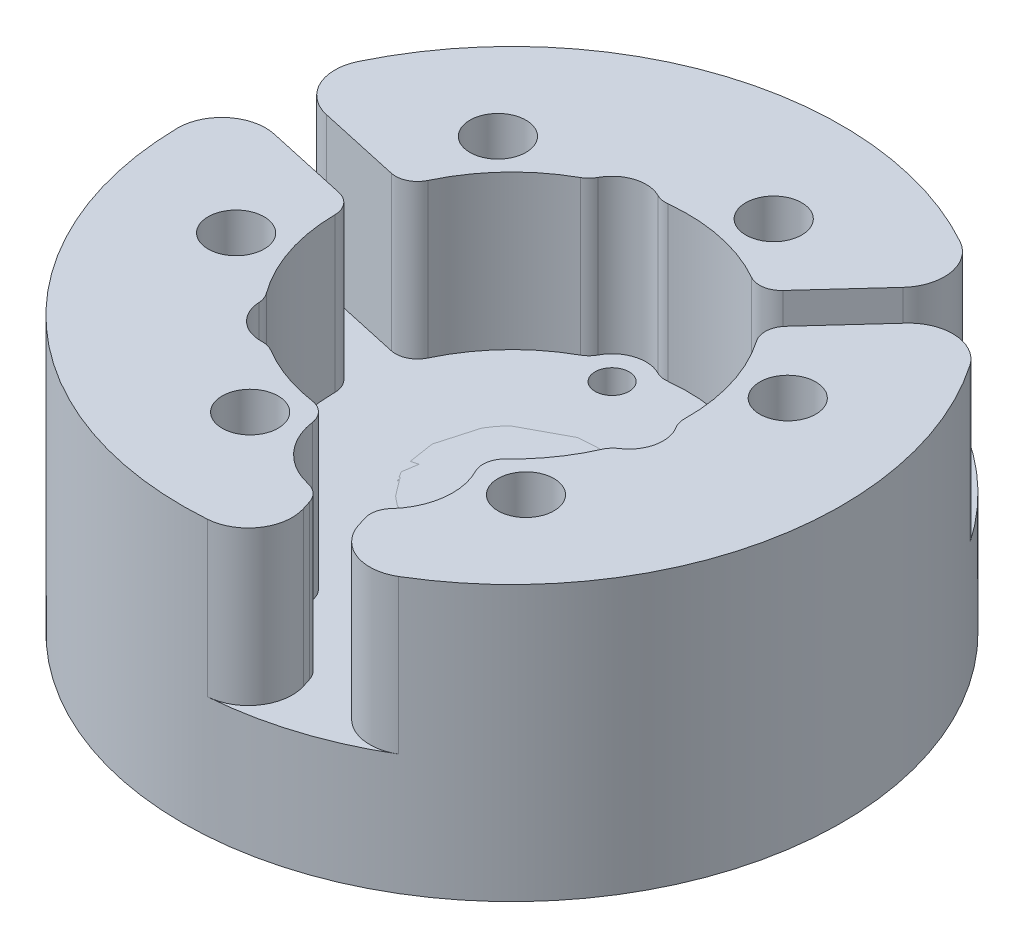
SolidWorks part; units mm, degrees
ref_plane "前视基准面" through (0, 0, 0) normal (0, 0, 1) x (1, 0, 0)
ref_plane "上视基准面" through (0, 0, 0) normal (0, 1, 0) x (1, 0, 0)
ref_plane "右视基准面" through (0, 0, 0) normal (1, 0, 0) x (0, 0, -1)
other "Configuration Table"
sketch "草图1" plane through (0, 0, 0) normal (0, 1, 0) x (1, 0, 0)
  circle A0 centre (0, 0) radius 30
  dimension "D1" = 60
extrude "凸台-拉伸1" add sketch "草图1" along normal blind 25
sketch "草图3" plane through (0, 25, 0) normal (0, 1, 0) x (1, 0, 0)
  circle A12 centre (-14.7658, 13.4896) radius 2.55
  circle A13 centre (4.2994, 19.5324) radius 2.55
  circle A14 centre (19.0653, 6.0428) radius 2.55
  circle A15 centre (14.7658, -13.4896) radius 2.55
  circle A16 centre (-4.2994, -19.5324) radius 2.55
  circle A17 centre (-19.0653, -6.0428) radius 2.55
  point P15 (0, 0)
  dimension "D1" = 6
extrude "切除-拉伸2" cut sketch "草图3" against normal through all
sketch "草图2" plane through (0, 25, 0) normal (0, 1, 0) x (1, 0, 0)
  line L0 (-19.0653, -6.0428) -> (-4.2994, -19.5324) construction
  line L1 (-11.6824, -12.7876) -> (0, 0) construction
  line L2 (-4.2994, -19.5324) -> (14.7658, -13.4896) construction
  line L3 (-1.2898, -5.8597) -> (4.4298, -4.0469)
  line L4 (4.4298, -4.0469) -> (5.7196, 1.8128)
  line L5 (5.7196, 1.8128) -> (1.2898, 5.8597)
  line L14 (5.2332, -16.511) -> (-5.2019, 16.4123) construction
  line L15 (1.2898, 5.8597) -> (-4.4298, 4.0469)
  line L16 (-4.4298, 4.0469) -> (-5.7196, -1.8128)
  line L17 (-5.7196, -1.8128) -> (-1.2898, -5.8597)
  circle A0 centre (0, 0) radius 5.1962 construction
  circle A1 centre (-4.23, 13.3457) radius 1.55
  circle A2 centre (13.6727, -3.0096) radius 1.55
  circle A3 centre (-9.4427, -10.3361) radius 1.55
  point P28 (0, 0)
  dimension "D1" = 3.1
  dimension "D2" = 14
  dimension "D3" = 6
  dimension "D4" = 3
extrude "切除-拉伸1" cut sketch "草图2" against normal through all
sketch "草图5" plane through (0, 25, 0) normal (0, 1, 0) x (1, 0, 0)
  line L3 (-1.0891, -13.94) -> (0.2828, -18.2683)
  line L4 (5.278, -21.4057) -> (8.0161, -20.5379)
  line L5 (10.2921, -15.0959) -> (8.9202, -10.7675)
  line L6 (-1.0891, -13.94) -> (0.2828, -18.2683)
  line L7 (5.278, -21.4057) -> (8.0161, -20.5379)
  line L8 (10.2921, -15.0959) -> (8.9202, -10.7675)
  arc A7 (0.2828, -18.2683) -> (2.0868, -20.8437) centre (5.2874, -16.6821) ccw
  arc A8 (2.0868, -20.8437) -> (5.278, -21.4057) centre (4.2206, -18.0693) ccw
  arc A9 (8.0161, -20.5379) -> (10.3009, -18.2402) centre (6.9586, -17.2015) ccw
  arc A10 (10.3009, -18.2402) -> (10.2921, -15.0959) centre (5.2874, -16.6821) ccw
  arc A11 (9.4319, -8.3546) -> (8.9202, -10.7675) centre (11.3034, -10.0122) ccw
  arc A12 (9.4319, -8.3546) -> (-2.8974, -12.2624) centre (0, 0) ccw
  arc A13 (-1.0891, -13.94) -> (-2.8974, -12.2624) centre (-3.4722, -14.6954) ccw
  arc A14 (0.2828, -18.2683) -> (2.0868, -20.8437) centre (5.2874, -16.6821) ccw
  arc A15 (2.0868, -20.8437) -> (5.278, -21.4057) centre (4.2206, -18.0693) ccw
  arc A16 (8.0161, -20.5379) -> (10.3009, -18.2402) centre (6.9586, -17.2015) ccw
  arc A17 (10.3009, -18.2402) -> (10.2921, -15.0959) centre (5.2874, -16.6821) ccw
  arc A18 (9.4319, -8.3546) -> (8.9202, -10.7675) centre (11.3034, -10.0122) ccw
  arc A19 (9.4319, -8.3546) -> (-2.8974, -12.2624) centre (0, 0) ccw
  arc A20 (-1.0891, -13.94) -> (-2.8974, -12.2624) centre (-3.4722, -14.6954) ccw
  dimension "D1" = 0
sketch "草图6" plane through (0, 25, 0) normal (0, 1, 0) x (1, 0, 0)
  circle A1 centre (0, 0) radius 16
  circle A2 centre (5.2874, -16.6821) radius 6
extrude "切除-拉伸4" cut sketch "草图6" against normal blind 14
sketch "草图8" plane through (0, 11, 0) normal (0, 1, 0) x (1, 0, 0)
  line L0 (0, 0) -> (-15106.966, 47663.1889) construction
  line L1 (-4.4298, 4.0469) -> (1.2898, 5.8597) construction
  line L2 (0, 0) -> (33724.0494, 36914.6108) construction
  line L3 (1.2898, 5.8597) -> (5.7196, 1.8128) construction
  line L4 (0, 0) -> (48831.0154, -10748.5781) construction
  line L5 (5.7196, 1.8128) -> (4.4298, -4.0469) construction
  line L6 (-35.3499, 7.7811) -> (-10.9344, 2.4069) construction
  line L7 (-34.92, 9.7344) -> (-10.5044, 4.3601)
  line L8 (-35.7798, 5.8279) -> (-11.3643, 0.4536)
  line L9 (-5.7196, -1.8128) -> (-4.4298, 4.0469) construction
  line L10 (24.4136, 26.7233) -> (7.5516, 8.266) construction
  line L11 (25.8902, 25.3744) -> (9.0282, 6.9171)
  line L12 (22.937, 28.0723) -> (6.075, 9.615)
  line L13 (10.9363, -34.5045) -> (3.3828, -10.6729) construction
  line L14 (9.0298, -35.1088) -> (1.4763, -11.2772)
  line L15 (12.8428, -33.9002) -> (5.2893, -10.0686)
  arc A0 (-34.92, 9.7344) -> (-35.7798, 5.8279) centre (-35.3499, 7.7811) ccw
  arc A1 (-11.3643, 0.4536) -> (-10.5044, 4.3601) centre (-10.9344, 2.4069) ccw
  arc A2 (25.8902, 25.3744) -> (22.937, 28.0723) centre (24.4136, 26.7233) ccw
  arc A3 (6.075, 9.615) -> (9.0282, 6.9171) centre (7.5516, 8.266) ccw
  arc A4 (9.0298, -35.1088) -> (12.8428, -33.9002) centre (10.9363, -34.5045) ccw
  arc A5 (5.2893, -10.0686) -> (1.4763, -11.2772) centre (3.3828, -10.6729) ccw
  point P5 (-1.57, 4.9533)
  point P10 (3.5047, 3.8363)
  point P15 (5.0747, -1.117)
  point P18 (-23.1421, 5.094)
  point P29 (15.9826, 17.4947)
  point P36 (7.1595, -22.5887)
  point P41 (0, 0)
  arc M2 (9.7578, -12.6801) -> (-0.672, -15.9859) centre (0, 0) ccw
  arc M3 (-0.672, -15.9859) -> (9.7578, -12.6801) centre (5.2874, -16.6821) ccw
  dimension "D3" = 2
  dimension "D1" = 25
  dimension "D2" = 6
  dimension "D4" = 3
extrude "切除-拉伸5" cut sketch "草图8" against normal up to surface (14 mm away) contours L7 A0 L8 M2 | L14 A4 L15 M3 | L11 A2 L12 M2
sketch "草图9" plane through (0, 0, 0) normal (0, -1, 0) x (1, 0, 0)
  circle A6 centre (-4.2994, 19.5324) radius 5.05
  circle A7 centre (14.7658, 13.4896) radius 5.05
  circle A8 centre (19.0653, -6.0428) radius 5.05
  circle A9 centre (4.2994, -19.5324) radius 5.05
  circle A10 centre (-14.7658, -13.4896) radius 5.05
  circle A11 centre (-19.0653, 6.0428) radius 5.05
  point P20 (0, 0)
  dimension "D1" = 6
extrude "切除-拉伸6" cut sketch "草图9" against normal blind 6
sketch "草图11" plane through (0, 25, 0) normal (0, 1, 0) x (1, 0, 0)
  circle A0 centre (-9.4427, -10.3361) radius 3.1
  circle A1 centre (13.6727, -3.0096) radius 3.1
  circle A2 centre (-4.23, 13.3457) radius 3.1
extrude "切除-拉伸7" cut sketch "草图11" against normal up to surface (14 mm away) up to face at (0.9454, 11, 2.9828)
fillet "圆角1" radius 4 6 edges at (-29.6634, 18, -4.4816) (10.9505, 18, 27.93) (21.666, 18, -20.7505) (18.7128, 18, -23.4485) (-28.8035, 18, -8.388) (7.1375, 18, 29.1386)
fillet "圆角2" radius 1 6 edges at (-4.4298, 5.5, -4.0469) (1.2898, 5.5, -5.8597) (5.7196, 5.5, -1.8128) (-1.2898, 5.5, 5.8597) (-5.7196, 5.5, 1.8128) (4.4298, 5.5, 4.0469)
fillet "圆角3" radius 2 14 edges at (-15.9333, 18, -1.4593) (-15.0734, 18, -5.3658) (-2.3675, 18, -15.8239) (-7.1799, 18, -14.2986) (9.2305, 18, -13.069) (14.8876, 18, 5.8616) (15.9729, 18, 0.9313) (9.7578, 18, 12.6801) (-0.672, 18, 15.9859) (8.9031, 18, 21.4703) (5.0901, 18, 22.6789) (-12.5201, 18, 9.9623) (-8.793, 18, 13.3672) (12.1836, 18, -10.3711)
sketch "草图12" plane through (0, 11, 0) normal (0, 1, 0) x (1, 0, 0)
  circle A12 centre (0, 0) radius 7.5
extrude "凸台-拉伸2" add sketch "草图12" against normal blind 2 separate body
sketch "草图13" plane through (0, 0, 0) normal (0, -1, 0) x (1, 0, 0)
  circle A0 centre (-4.23, -13.3457) radius 1.55 construction
  circle A1 centre (13.6727, 3.0096) radius 1.55 construction
  circle A2 centre (-9.4427, 10.3361) radius 1.55 construction
  circle A3 centre (-19.0653, 6.0428) radius 2.55 construction
  circle A4 centre (-19.0653, 6.0428) radius 5.05 construction
  circle A5 centre (-14.7658, -13.4896) radius 2.55 construction
  circle A6 centre (-14.7658, -13.4896) radius 5.05 construction
  circle A7 centre (4.2994, -19.5324) radius 2.55 construction
  circle A8 centre (4.2994, -19.5324) radius 5.05 construction
  circle A9 centre (19.0653, -6.0428) radius 2.55 construction
  circle A10 centre (19.0653, -6.0428) radius 5.05 construction
  circle A11 centre (14.7658, 13.4896) radius 2.55 construction
  circle A12 centre (14.7658, 13.4896) radius 5.05 construction
  circle A13 centre (-4.2994, 19.5324) radius 2.55 construction
  circle A14 centre (-4.2994, 19.5324) radius 5.05 construction
  circle A15 centre (0, 0) radius 30 construction
  circle A16 centre (-4.23, -13.3457) radius 1.55
  circle A17 centre (13.6727, 3.0096) radius 1.55
  circle A18 centre (-9.4427, 10.3361) radius 1.55
  circle A19 centre (-19.0653, 6.0428) radius 2.55
  circle A20 centre (-19.0653, 6.0428) radius 5.05
  circle A21 centre (-14.7658, -13.4896) radius 2.55
  circle A22 centre (-14.7658, -13.4896) radius 5.05
  circle A23 centre (4.2994, -19.5324) radius 2.55
  circle A24 centre (4.2994, -19.5324) radius 5.05
  circle A25 centre (19.0653, -6.0428) radius 2.55
  circle A26 centre (19.0653, -6.0428) radius 5.05
  circle A27 centre (14.7658, 13.4896) radius 2.55
  circle A28 centre (14.7658, 13.4896) radius 5.05
  circle A29 centre (-4.2994, 19.5324) radius 2.55
  circle A30 centre (-4.2994, 19.5324) radius 5.05
  circle A31 centre (0, 0) radius 30
  point P42 (0, 0)
  point P43 (0, 0)
